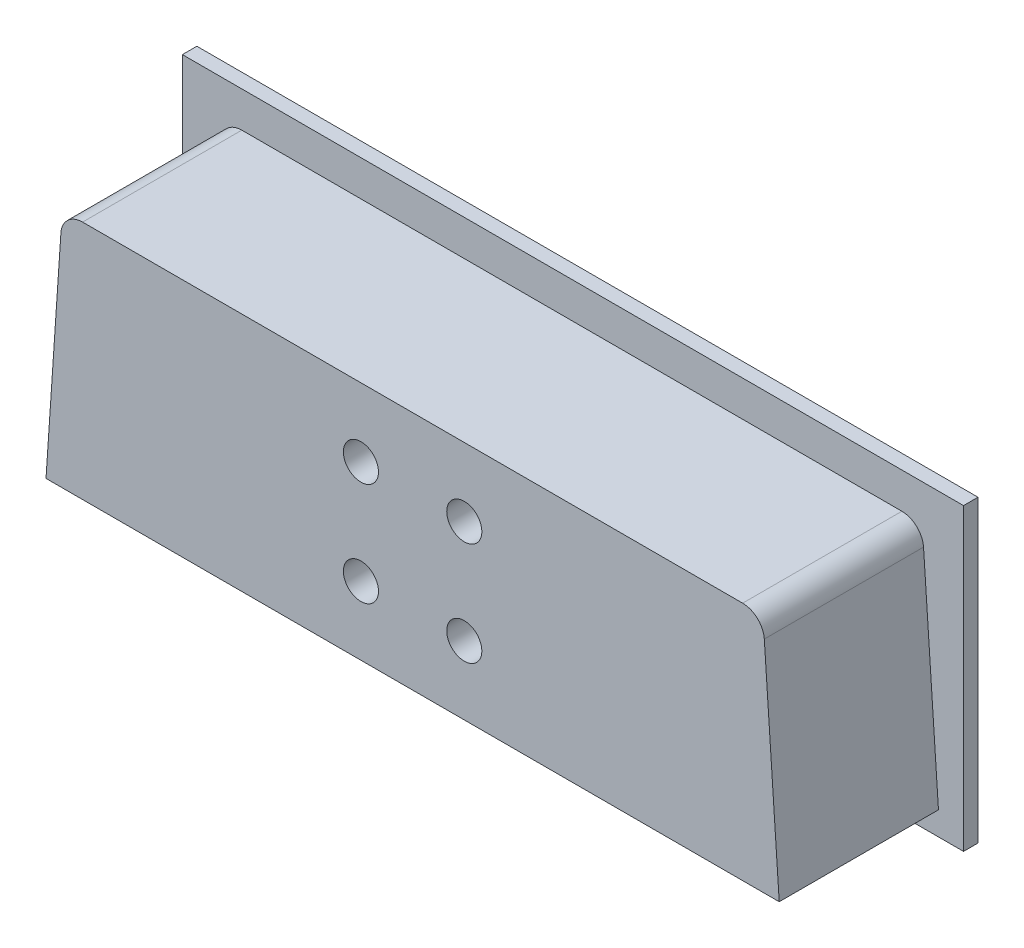
SolidWorks part; units mm, degrees
ref_plane "Přední rovina" through (0, 0, 0) normal (0, 0, 1) x (1, 0, 0)
ref_plane "Horní rovina" through (0, 0, 0) normal (0, 1, 0) x (1, 0, 0)
ref_plane "Pravá rovina" through (0, 0, 0) normal (1, 0, 0) x (0, 0, -1)
sketch "Skica1" plane through (0, 0, 0) normal (0, 0, 1) x (1, 0, 0)
  line L0 (50.65, 33.2) -> (50.65, 0) construction
  line L1 (0, 0) -> (101.3, 0)
  line L2 (0, 0) -> (2.25, 33.2)
  line L3 (2.25, 33.2) -> (99.05, 33.2)
  line L4 (101.3, 0) -> (99.05, 33.2)
  dimension "D1" = 33.2
  dimension "D2" = 96.8
  dimension "D3" = 101.3
extrude "Přidat vysunutím1" add sketch "Skica1" along normal blind 22
fillet "Zaoblit1" radius 3 2 edges at (2.25, 33.2, 11) (99.05, 33.2, 11)
sketch "Skica2" plane through (0, 0, 0) normal (0, 0, -1) x (-1, 0, 0)
  line L0 (-96.2464, 33.2) -> (-5.0536, 33.2) construction
  line L1 (-104.7633, 38.1358) -> (3.1553, 38.1358)
  line L2 (-104.7633, 38.1358) -> (-104.7633, -3.245)
  line L3 (-104.7633, -3.245) -> (3.1553, -3.245)
  line L4 (3.1553, 38.1358) -> (3.1553, -3.245)
  dimension "D1" = 41.3808
  dimension "D2" = 107.9186
extrude "Přidat vysunutím2" add sketch "Skica2" along normal blind 2
sketch "Skica3" plane through (0, 0, 22) normal (0, 0, 1) x (1, 0, 0)
  line L0 (75.65, 42.6879) -> (75.65, -16.3954) construction
  line L1 (104.7633, 38.1358) -> (104.7633, -3.245) construction
  line L2 (25.65, 46.6511) -> (25.65, -13.4611) construction
  line L3 (-3.1553, -3.245) -> (-3.1553, 38.1358) construction
  line L4 (25.65, 16.595) -> (75.65, 16.595) construction
  line L5 (50.65, 33.2) -> (50.65, 0) construction
  line L6 (96.2464, 33.2) -> (5.0536, 33.2) construction
  line L7 (0, 0) -> (101.3, 0) construction
  circle A0 centre (57.79, 9.455) radius 2.425
  circle A1 centre (43.51, 9.455) radius 2.425
  circle A2 centre (57.79, 23.735) radius 2.425
  circle A3 centre (43.51, 23.735) radius 2.425
  point P26 (0, 0)
  dimension "D3" = 4.85
  dimension "D1" = 25.65
  dimension "D2" = 25.65
  dimension "D4" = 7.14
  dimension "D5" = 7.14
  dimension "D6" = 7.14
  dimension "D7" = 7.14
extrude "Odebrat vysunutím1" cut sketch "Skica3" against normal blind 8.5
